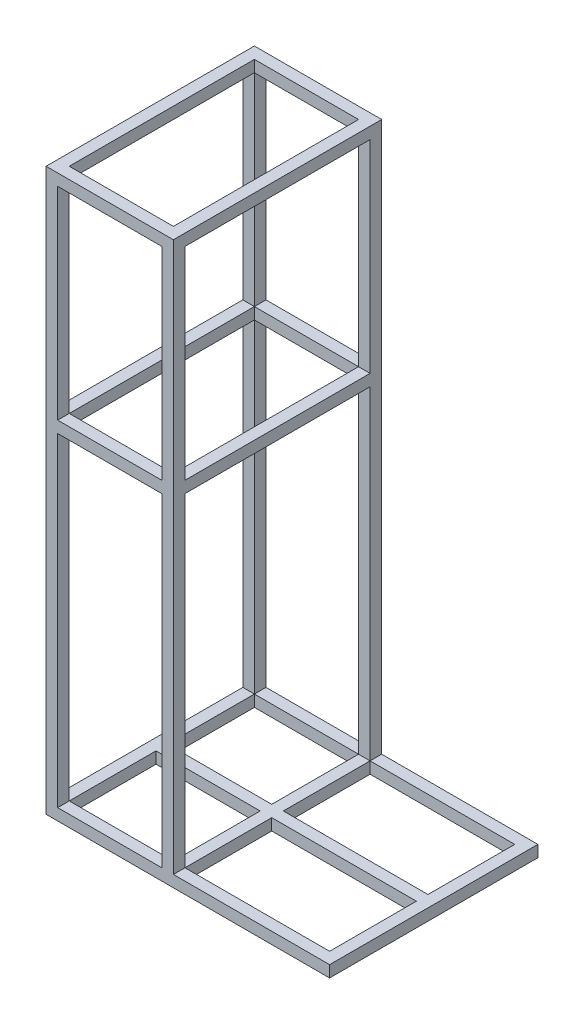
SolidWorks part; units mm, degrees
ref_plane "Front Plane" through (0, 0, 0) normal (0, 0, 1) x (1, 0, 0)
ref_plane "Top Plane" through (0, 0, 0) normal (0, 1, 0) x (1, 0, 0)
ref_plane "Right Plane" through (0, 0, 0) normal (1, 0, 0) x (0, 0, -1)
sketch "Sketch1" plane through (0, 0, 0) normal (0, 1, 0) x (1, 0, 0)
  line L1 (0, 0) -> (-25.4, 0)
  line L2 (0, 0) -> (0, 25.4)
  line L3 (0, 25.4) -> (-25.4, 25.4)
  line L4 (-25.4, 0) -> (-25.4, 25.4)
  line L5 (-25.4, 431.8) -> (0, 431.8)
  line L6 (-25.4, 431.8) -> (-25.4, 457.2)
  line L7 (-25.4, 457.2) -> (0, 457.2)
  line L8 (0, 431.8) -> (0, 457.2)
  line L9 (228.6, 0) -> (254, 0)
  line L10 (228.6, 0) -> (228.6, 25.4)
  line L11 (228.6, 25.4) -> (254, 25.4)
  line L12 (254, 0) -> (254, 25.4)
  line L13 (228.6, 431.8) -> (254, 431.8)
  line L14 (228.6, 431.8) -> (228.6, 457.2)
  line L15 (228.6, 457.2) -> (254, 457.2)
  line L16 (254, 431.8) -> (254, 457.2)
  dimension "D1" = 25.4
  dimension "D2" = 457.2
  dimension "D3" = 279.4
extrude "Boss-Extrude1" add sketch "Sketch1" along normal blind 1231.9
sketch "Sketch2" plane through (0, 0, 0) normal (1, 0, 0) x (0, 0, -1)
  line L0 (25.4, 1231.9) -> (25.4, 0) construction
  line L1 (0, 0) -> (25.4, 0)
  line L2 (0, 0) -> (0, 25.4)
  line L3 (0, 25.4) -> (25.4, 25.4)
  line L4 (25.4, 0) -> (25.4, 25.4)
  line L5 (457.2, 1231.9) -> (457.2, 0) construction
  line L6 (431.8, 0) -> (457.2, 0)
  line L7 (431.8, 0) -> (431.8, 25.4)
  line L8 (431.8, 25.4) -> (457.2, 25.4)
  line L9 (457.2, 0) -> (457.2, 25.4)
  line L10 (228.6, 25.4) -> (228.6, 0) construction
  line L11 (215.9, 0) -> (241.3, 0)
  line L12 (215.9, 0) -> (215.9, 25.4)
  line L13 (215.9, 25.4) -> (241.3, 25.4)
  line L14 (241.3, 0) -> (241.3, 25.4)
extrude "Boss-Extrude2" add sketch "Sketch2" along normal blind 596.9
sketch "Sketch3" plane through (0, 0, -25.4) normal (0, 0, -1) x (-1, 0, 0)
  line L0 (-596.9, 25.4) -> (-254, 25.4) construction
  line L1 (25.4, 0) -> (0, 0)
  line L2 (25.4, 0) -> (25.4, 25.4)
  line L3 (25.4, 25.4) -> (0, 25.4)
  line L4 (0, 0) -> (0, 25.4)
  line L5 (-596.9, 0) -> (-571.5, 0)
  line L6 (-596.9, 0) -> (-596.9, 25.4)
  line L7 (-596.9, 25.4) -> (-571.5, 25.4)
  line L8 (-571.5, 0) -> (-571.5, 25.4)
extrude "Boss-Extrude3" add sketch "Sketch3" along normal through all
sketch "Sketch4" plane through (0, 0, -431.8) normal (0, 0, 1) x (1, 0, 0)
  line L0 (-25.4, 0) -> (596.9, 0) construction
  line L1 (254, 25.4) -> (228.6, 25.4)
  line L2 (254, 25.4) -> (254, 0)
  line L3 (254, 0) -> (228.6, 0)
  line L4 (228.6, 25.4) -> (228.6, 0)
  line L5 (254, 1231.9) -> (254, 25.4) construction
  line L6 (228.6, 1231.9) -> (254, 1231.9)
  line L7 (228.6, 1231.9) -> (228.6, 1206.5)
  line L8 (228.6, 1206.5) -> (254, 1206.5)
  line L9 (254, 1231.9) -> (254, 1206.5)
  line L10 (-25.4, 1231.9) -> (-25.4, 0) construction
  line L11 (0, 1231.9) -> (-25.4, 1231.9)
  line L12 (0, 1231.9) -> (0, 1206.5)
  line L13 (0, 1206.5) -> (-25.4, 1206.5)
  line L14 (-25.4, 1231.9) -> (-25.4, 1206.5)
  line L15 (228.6, 1231.9) -> (228.6, 25.4) construction
  line L16 (254, 762) -> (228.6, 762)
  line L17 (254, 762) -> (254, 736.6)
  line L18 (254, 736.6) -> (228.6, 736.6)
  line L19 (228.6, 762) -> (228.6, 736.6)
  line L20 (0, 1231.9) -> (0, 25.4) construction
  line L21 (0, 762) -> (-25.4, 762)
  line L22 (0, 762) -> (0, 736.6)
  line L23 (0, 736.6) -> (-25.4, 736.6)
  line L24 (-25.4, 762) -> (-25.4, 736.6)
  line L25 (228.6, 25.4) -> (0, 25.4) construction
  dimension "D1" = 762
extrude "Boss-Extrude4" add sketch "Sketch4" along normal through all
sketch "Sketch5" plane through (0, 0, 0) normal (1, 0, 0) x (0, 0, -1)
  line L0 (457.2, 1231.9) -> (457.2, 25.4) construction
  line L1 (0, 1231.9) -> (25.4, 1231.9)
  line L2 (0, 1231.9) -> (0, 1206.5)
  line L3 (0, 1206.5) -> (25.4, 1206.5)
  line L4 (25.4, 1231.9) -> (25.4, 1206.5)
  line L5 (431.8, 1206.5) -> (457.2, 1206.5)
  line L6 (431.8, 1206.5) -> (431.8, 1231.9)
  line L7 (431.8, 1231.9) -> (457.2, 1231.9)
  line L8 (457.2, 1206.5) -> (457.2, 1231.9)
  line L9 (431.8, 762) -> (457.2, 762)
  line L10 (431.8, 762) -> (431.8, 736.6)
  line L11 (431.8, 736.6) -> (457.2, 736.6)
  line L12 (457.2, 762) -> (457.2, 736.6)
  line L13 (0, 1231.9) -> (0, 25.4) construction
  line L14 (25.4, 762) -> (0, 762)
  line L15 (25.4, 762) -> (25.4, 736.6)
  line L16 (25.4, 736.6) -> (0, 736.6)
  line L17 (0, 762) -> (0, 736.6)
extrude "Boss-Extrude5" add sketch "Sketch5" along normal up to next
